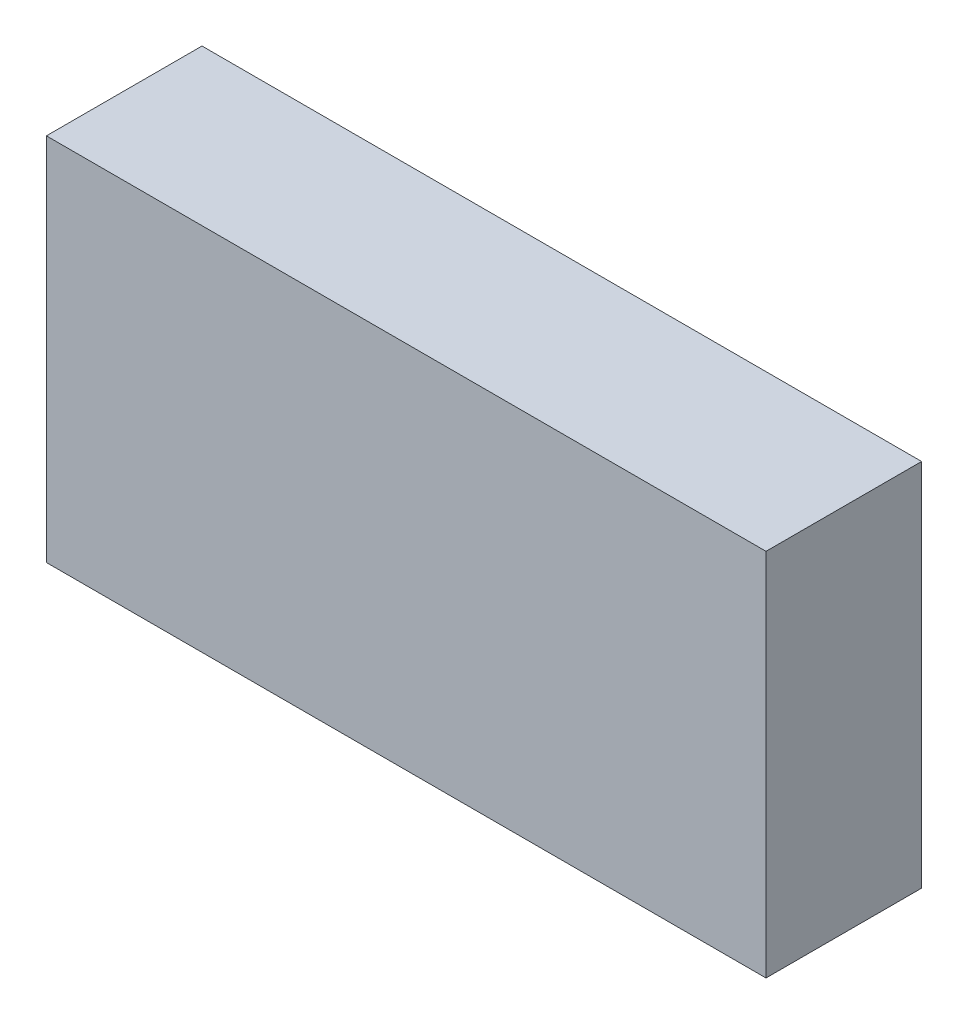
SolidWorks part; units mm, degrees
ref_plane "Front Plane" through (0, 0, 0) normal (0, 0, 1) x (1, 0, 0)
ref_plane "Top Plane" through (0, 0, 0) normal (0, 1, 0) x (1, 0, 0)
ref_plane "Right Plane" through (0, 0, 0) normal (1, 0, 0) x (0, 0, -1)
sketch "Sketch1" plane through (0, 0, 0) normal (0, 0, 1) x (1, 0, 0)
  line L1 (-18.5, 9.5) -> (18.5, 9.5)
  line L2 (-18.5, 9.5) -> (-18.5, -9.5)
  line L3 (-18.5, -9.5) -> (18.5, -9.5)
  line L4 (18.5, 9.5) -> (18.5, -9.5)
  line L5 (-18.5, 9.5) -> (18.5, -9.5) construction
  line L6 (-18.5, -9.5) -> (18.5, 9.5) construction
  point P0 (0, 0)
  dimension "D1" = 19
  dimension "D2" = 37
extrude "Boss-Extrude1" add sketch "Sketch1" along normal mid plane 8
